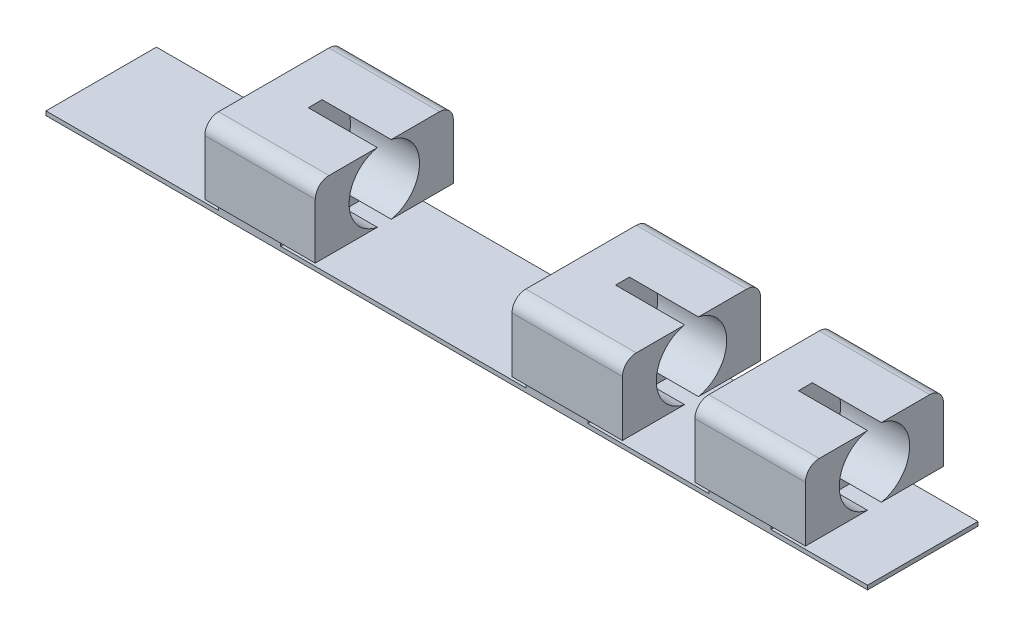
SolidWorks part; units mm, degrees
ref_plane "Front Plane" through (0, 0, 0) normal (0, 0, 1) x (1, 0, 0)
ref_plane "Top Plane" through (0, 0, 0) normal (0, 1, 0) x (1, 0, 0)
ref_plane "Right Plane" through (0, 0, 0) normal (1, 0, 0) x (0, 0, -1)
sketch "Sketch2" plane through (0, 0, 0) normal (0, 1, 0) x (1, 0, 0)
  line L1 (-56, 8) -> (56, 8)
  line L2 (-56, 8) -> (-56, -8)
  line L3 (-56, -8) -> (56, -8)
  line L5 (-56, 8) -> (56, -8) construction
  line L6 (-56, -8) -> (56, 8) construction
  line L7 (56, 8) -> (63, 8)
  line L9 (56, -8) -> (63, -8)
  line L10 (63, 8) -> (63, -8)
  point P0 (0, 0)
  dimension "D1" = 112
  dimension "D2" = 16
  dimension "D3" = 7
extrude "Boss-Extrude1" add sketch "Sketch2" against normal blind 0.6
sketch "Sketch3" plane through (0, 0, 0) normal (0, 1, 0) x (1, 0, 0)
  line L0 (29.5, 8) -> (29.5, -8) construction
  line L1 (63, 8) -> (-56, 8) construction
  line L2 (-56, -8) -> (63, -8) construction
  line L3 (-15, 8) -> (-15, -8) construction
  line L6 (56, 8) -> (56, -8) construction
  line L11 (40, 8) -> (49, 8)
  line L12 (40, 8) -> (40, -8)
  line L13 (40, -8) -> (49, -8)
  line L14 (49, 8) -> (49, -8)
  line L15 (13.5, 8) -> (22.5, 8)
  line L16 (13.5, 8) -> (13.5, -8)
  line L17 (13.5, -8) -> (22.5, -8)
  line L18 (22.5, 8) -> (22.5, -8)
  line L19 (-31, 8) -> (-22, 8)
  line L20 (-31, 8) -> (-31, -8)
  line L21 (-31, -8) -> (-22, -8)
  line L22 (-22, 8) -> (-22, -8)
  line L24 (63, 8) -> (-56, 8) construction
  line L25 (-56, -8) -> (63, -8) construction
  line L26 (63, -8) -> (63, 8) construction
  dimension "D2" = 44.5
  dimension "D3" = 16
  dimension "D4" = 0
  dimension "D5" = 7
  dimension "D6" = 9
  dimension "D7" = 9
  dimension "D8" = 7
  dimension "D9" = 9
  dimension "D10" = 7
  dimension "D11" = 7
  dimension "D12" = 26.5
extrude "Boss-Extrude2" add sketch "Sketch3" along normal blind 2.4
sketch "Sketch4" plane through (0, 2.4, 0) normal (0, 1, 0) x (1, 0, 0)
  line L10 (-31, 8) -> (-56, 8) construction
  line L11 (-31, 10) -> (-15, 10)
  line L19 (-31, 10) -> (-31, -10)
  line L20 (-31, -10) -> (-15, -10)
  line L21 (-15, 10) -> (-15, -10)
  line L22 (-22, -8) -> (-22, 8) construction
  line L23 (22.5, 8) -> (13.5, 8) construction
  line L24 (13.5, 10) -> (29.5, 10)
  line L25 (13.5, 10) -> (13.5, -10)
  line L26 (13.5, -10) -> (29.5, -10)
  line L27 (29.5, 10) -> (29.5, -10)
  line L28 (22.5, -8) -> (22.5, 8) construction
  line L29 (63, -8) -> (63, 8) construction
  line L30 (40, 10) -> (56, 10)
  line L31 (40, 10) -> (40, -10)
  line L32 (40, -10) -> (56, -10)
  line L33 (56, 10) -> (56, -10)
  dimension "D1" = 7
  dimension "D2" = 2
  dimension "D3" = 7
  dimension "D4" = 2
  dimension "D5" = 7
extrude "Boss-Extrude3" add sketch "Sketch4" along normal blind 10
sketch "Sketch5" plane through (56, 0, 0) normal (1, 0, 0) x (0, 0, -1)
  line L0 (0, 12.5) -> (0, 2.3) construction
  circle A0 centre (0, 7.4) radius 5.1
  dimension "D1" = 10.2
extrude "Cut-Extrude1" cut sketch "Sketch5" against normal blind 10
sketch "Sketch6" plane through (29.5, 0, 0) normal (1, 0, 0) x (0, 0, -1)
  line L0 (0, 12.4) -> (0, 2.4) construction
  circle A2 centre (0, 7.4) radius 5.1
  dimension "D1" = 10.2
extrude "Cut-Extrude3" cut sketch "Sketch6" against normal blind 10
sketch "Sketch7" plane through (-15, 0, 0) normal (1, 0, 0) x (0, 0, -1)
  line L0 (0, 12.4) -> (0, 2.4) construction
  circle A1 centre (0, 7.4) radius 5.1
  dimension "D1" = 10.2
extrude "Cut-Extrude4" cut sketch "Sketch7" against normal blind 10
fillet "Fillet1" radius 2 6 edges at (48, 12.4, -10) (48, 12.4, 10) (21.5, 12.4, -10) (21.5, 12.4, 10) (-23, 12.4, -10) (-23, 12.4, 10)
sketch "Sketch8" plane through (-31, 0, 0) normal (-1, 0, 0) x (0, 0, 1)
  line L0 (0, 12.4) -> (0, 2.4) construction
  line L2 (-8, 2.4) -> (8, 2.4) construction
  line L3 (-8, 2.4) -> (-8, 0) construction
  line L4 (8, 2.4) -> (8, 0) construction
  line L5 (-6, 7.4) -> (6, 7.4) construction
  line L6 (7.1, 6.3) -> (4.9, 6.3)
  line L7 (-7.1, 8.5) -> (-4.9, 8.5)
  line L8 (-7.1, 8.5) -> (-7.1, 6.3)
  line L9 (-7.1, 6.3) -> (-4.9, 6.3)
  line L10 (-4.9, 8.5) -> (-4.9, 6.3)
  line L11 (-7.1, 8.5) -> (-4.9, 6.3) construction
  line L12 (-7.1, 6.3) -> (-4.9, 8.5) construction
  line L13 (7.1, 8.5) -> (7.1, 6.3)
  line L14 (4.9, 8.5) -> (4.9, 6.3)
  line L15 (7.1, 8.5) -> (4.9, 8.5)
  point P14 (0, 7.4)
  dimension "D2" = 12
  dimension "D3" = 2.2
  dimension "D4" = 2.2
sketch "Sketch9" plane through (13.5, 0, -13.5) normal (-1, 0, 0) x (0, 0, 1)
  line L0 (13.5, 12.4) -> (13.5, 2.4) construction
  line L1 (5.5, 12.4) -> (21.5, 12.4) construction
  line L5 (7.5, 7.4) -> (19.5, 7.4) construction
  line L6 (20.6, 6.3) -> (18.4, 6.3)
  line L7 (6.4, 8.5) -> (8.6, 8.5)
  line L8 (6.4, 8.5) -> (6.4, 6.3)
  line L9 (6.4, 6.3) -> (8.6, 6.3)
  line L10 (8.6, 8.5) -> (8.6, 6.3)
  line L11 (6.4, 8.5) -> (8.6, 6.3) construction
  line L12 (6.4, 6.3) -> (8.6, 8.5) construction
  line L13 (20.6, 8.5) -> (20.6, 6.3)
  line L14 (18.4, 8.5) -> (18.4, 6.3)
  line L15 (20.6, 8.5) -> (18.4, 8.5)
  point P9 (13.5, 12.4)
  point P14 (13.5, 7.4)
  dimension "D1" = 10
  dimension "D2" = 12
  dimension "D3" = 2.2
  dimension "D4" = 2.2
sketch "Sketch10" plane through (40, 0, -40) normal (-1, 0, 0) x (0, 0, 1)
  line L0 (40, 12.4) -> (40, 2.4) construction
  line L1 (32, 12.4) -> (48, 12.4) construction
  line L5 (34, 7.4) -> (46, 7.4) construction
  line L6 (47.1, 6.3) -> (44.9, 6.3)
  line L7 (32.9, 8.5) -> (35.1, 8.5)
  line L8 (32.9, 8.5) -> (32.9, 6.3)
  line L9 (32.9, 6.3) -> (35.1, 6.3)
  line L10 (35.1, 8.5) -> (35.1, 6.3)
  line L11 (32.9, 8.5) -> (35.1, 6.3) construction
  line L12 (32.9, 6.3) -> (35.1, 8.5) construction
  line L13 (47.1, 8.5) -> (47.1, 6.3)
  line L14 (44.9, 8.5) -> (44.9, 6.3)
  line L15 (47.1, 8.5) -> (44.9, 8.5)
  point P9 (40, 12.4)
  point P14 (40, 7.4)
  dimension "D2" = 12
  dimension "D3" = 2.2
  dimension "D4" = 2.2
extrude "Cut-Extrude5" cut sketch "Sketch8" against normal blind 3
extrude "Cut-Extrude6" cut sketch "Sketch9" against normal blind 3
extrude "Cut-Extrude7" cut sketch "Sketch10" against normal blind 3
